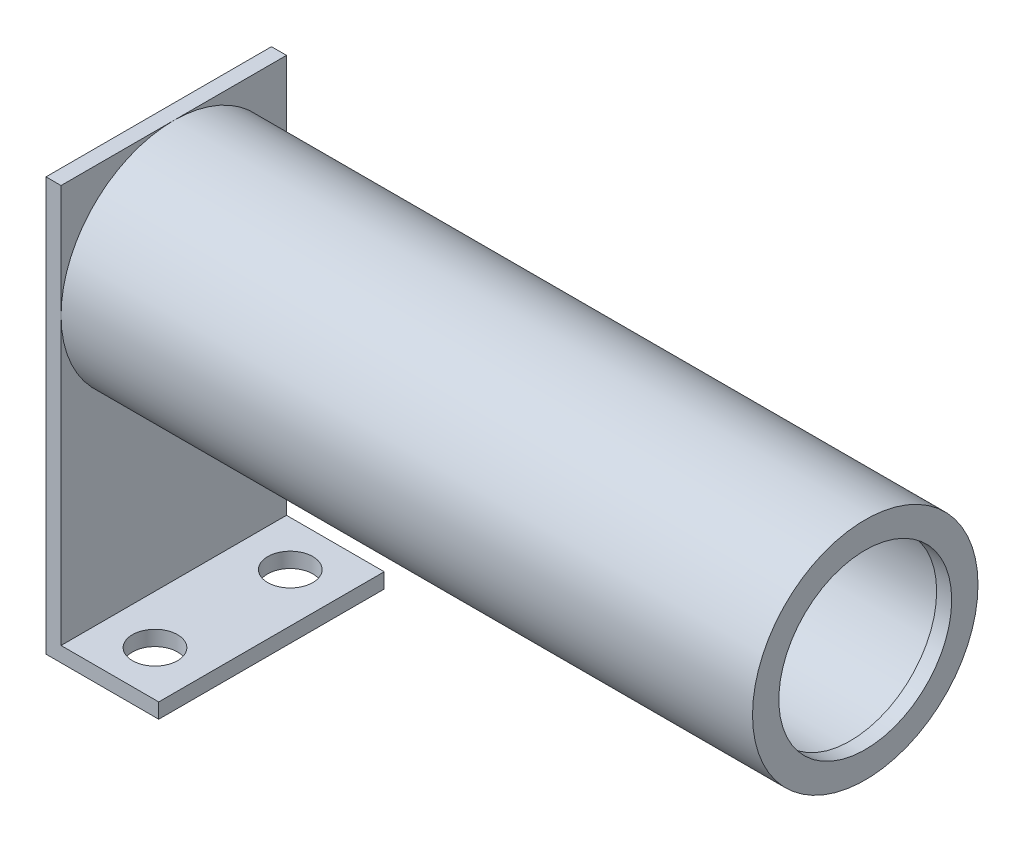
SolidWorks part; units mm, degrees
material "2024-O"
ref_plane "Front Plane" through (0, 0, 0) normal (0, 0, 1) x (1, 0, 0)
ref_plane "Top Plane" through (0, 0, 0) normal (0, 1, 0) x (1, 0, 0)
ref_plane "Right Plane" through (0, 0, 0) normal (1, 0, 0) x (0, 0, -1)
sketch "Sketch1" plane through (0, 0, 0) normal (0, 1, 0) x (1, 0, 0)
  line L1 (7.5, -15) -> (-7.5, -15)
  line L2 (7.5, -15) -> (7.5, 15)
  line L3 (7.5, 15) -> (-7.5, 15)
  line L4 (-7.5, -15) -> (-7.5, 15)
  line L5 (7.5, -15) -> (-7.5, 15) construction
  line L6 (7.5, 15) -> (-7.5, -15) construction
  point P0 (0, 0)
  dimension "D1" = 15
  dimension "D2" = 30
extrude "Boss-Extrude1" add sketch "Sketch1" along normal blind 2
sketch "Sketch2" plane through (0, 2, 0) normal (0, 1, 0) x (1, 0, 0)
  line L0 (-7.5, 15) -> (-5.5, 15)
  line L1 (7.5, 15) -> (-7.5, 15) construction
  line L2 (-5.5, 15) -> (-5.5, -15)
  line L3 (-7.5, -15) -> (7.5, -15) construction
  line L4 (-5.5, -15) -> (-7.5, -15)
  line L5 (-7.5, -15) -> (-7.5, 15)
  dimension "D1" = 2
extrude "Boss-Extrude2" add sketch "Sketch2" along normal blind 53
sketch "Sketch3" plane through (-5.5, 0, 0) normal (1, 0, 0) x (0, 0, -1)
  line L0 (0, 55) -> (0, 40) construction
  line L1 (-15, 55) -> (15, 55) construction
  circle A0 centre (0, 40) radius 15
  circle A1 centre (0, 40) radius 12.5
  dimension "D1" = 30
  dimension "D2" = 25
  dimension "D3" = 15
extrude "Boss-Extrude3" add sketch "Sketch3" along normal blind 92
sketch "Sketch4" plane through (86.5, 0, 0) normal (1, 0, 0) x (0, 0, -1)
  circle A1 centre (0, 40) radius 12.5
  circle A2 centre (0, 40) radius 11.5
  dimension "D1" = 25
  dimension "D2" = 1
extrude "Boss-Extrude4" add sketch "Sketch4" against normal blind 2
sketch "Sketch5" plane through (-5.5, 0, 0) normal (1, 0, 0) x (0, 0, -1)
  circle A0 centre (0, 40) radius 12.4
  circle A1 centre (0, 40) radius 6.4
  dimension "D1" = 24.8
  dimension "D3" = 12.8
  dimension "D2" = 6
extrude "Boss-Extrude5" [suppressed] add sketch "Sketch5" along normal blind 2 separate body
sketch "Sketch6" [suppressed] plane through (-3.5, 0, 0) normal (1, 0, 0) x (0, 0, -1)
  circle A1 centre (0, 40) radius 10.4
  circle A2 centre (0, 40) radius 8.4
  circle A3 centre (0, 40) radius 8.4
  dimension "D3" = 16.8
  dimension "D1" = 2
  dimension "D2" = 2
extrude "Boss-Extrude6" [suppressed] add sketch "Sketch6" along normal blind 94
sketch3d "3DSketch1"
  point P0 (7.5, 1.0314, -15)
sketch "Sketch7" plane through (0, 2, 0) normal (0, 1, 0) x (1, 0, 0)
  line L0 (1, -15) -> (1, -9) construction
  line L1 (-5.5, -15) -> (7.5, -15) construction
  line L2 (0, 0) -> (4.701, 0) construction
  circle A0 centre (1, -9) radius 3
  circle A1 centre (1, 9) radius 3
  dimension "D1" = 6
  dimension "D2" = 6
extrude "Cut-Extrude1" cut sketch "Sketch7" against normal blind 10
